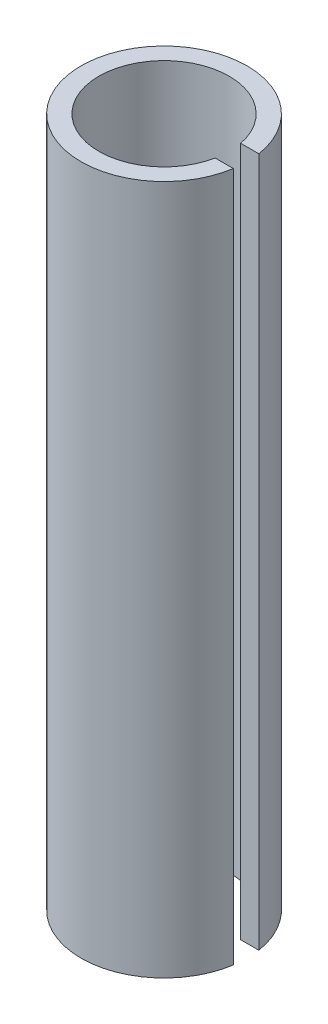
SolidWorks part; units mm, degrees
ref_plane "Front Plane" through (0, 0, 0) normal (0, 0, 1) x (1, 0, 0)
ref_plane "Top Plane" through (0, 0, 0) normal (0, 1, 0) x (1, 0, 0)
ref_plane "Right Plane" through (0, 0, 0) normal (1, 0, 0) x (0, 0, -1)
sketch "Sketch1" plane through (0, 0, 0) normal (0, 1, 0) x (1, 0, 0)
  line L0 (2.5005, 0.5) -> (3.2113, 0.5)
  line L1 (2.5005, -0.5) -> (3.2113, -0.5)
  line L2 (0, 0) -> (3.25, 0) construction
  circle A0 centre (0, 0) radius 3.25
  circle A1 centre (0, 0) radius 2.55
  dimension "D1" = 5.1
  dimension "D2" = 6.5
  dimension "D3" = 1
  dimension "D4" = 0.5
extrude "Boss-Extrude1" add sketch "Sketch1" along normal blind 27 contours A1 L0 A0 L1
